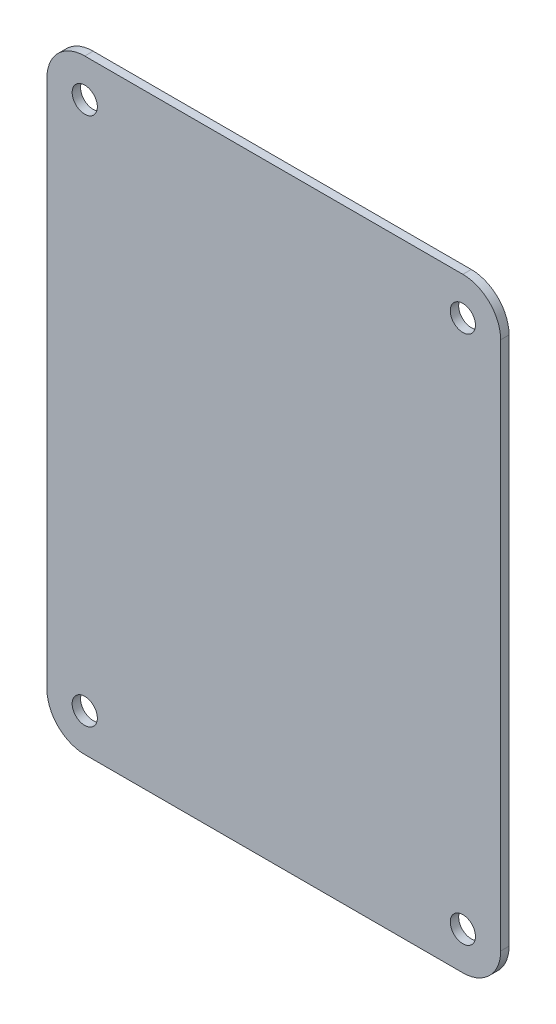
SolidWorks part; units mm, degrees
ref_plane "Alzado" through (0, 0, 0) normal (0, 0, 1) x (1, 0, 0)
ref_plane "Planta" through (0, 0, 0) normal (0, 1, 0) x (1, 0, 0)
ref_plane "Vista lateral" through (0, 0, 0) normal (1, 0, 0) x (0, 0, -1)
sketch "Model" plane through (0, 0, 0) normal (0, 0, 1) x (1, 0, 0)
  line L0 (-105.9434, 119.0565) -> (-105.9434, 56.0565)
  line L1 (-101.4434, 51.5565) -> (-56.4434, 51.5565)
  line L2 (-51.9434, 56.0565) -> (-51.9434, 119.0565)
  line L3 (-56.4434, 123.5565) -> (-101.4434, 123.5565)
  circle A0 centre (-101.4434, 119.0565) radius 1.5
  circle A1 centre (-56.4434, 119.0565) radius 1.5
  arc A2 (-101.4434, 123.5565) -> (-105.9434, 119.0565) centre (-101.4434, 119.0565) ccw
  arc A3 (-51.9434, 119.0565) -> (-56.4434, 123.5565) centre (-56.4434, 119.0565) ccw
  arc A4 (-105.9434, 56.0565) -> (-101.4434, 51.5565) centre (-101.4434, 56.0565) ccw
  arc A5 (-56.4434, 51.5565) -> (-51.9434, 56.0565) centre (-56.4434, 56.0565) ccw
  circle A6 centre (-101.4434, 56.0565) radius 1.5
  circle A7 centre (-56.4434, 56.0565) radius 1.5
extrude "Saliente-Extruir1" add sketch "Model" along normal blind 1
